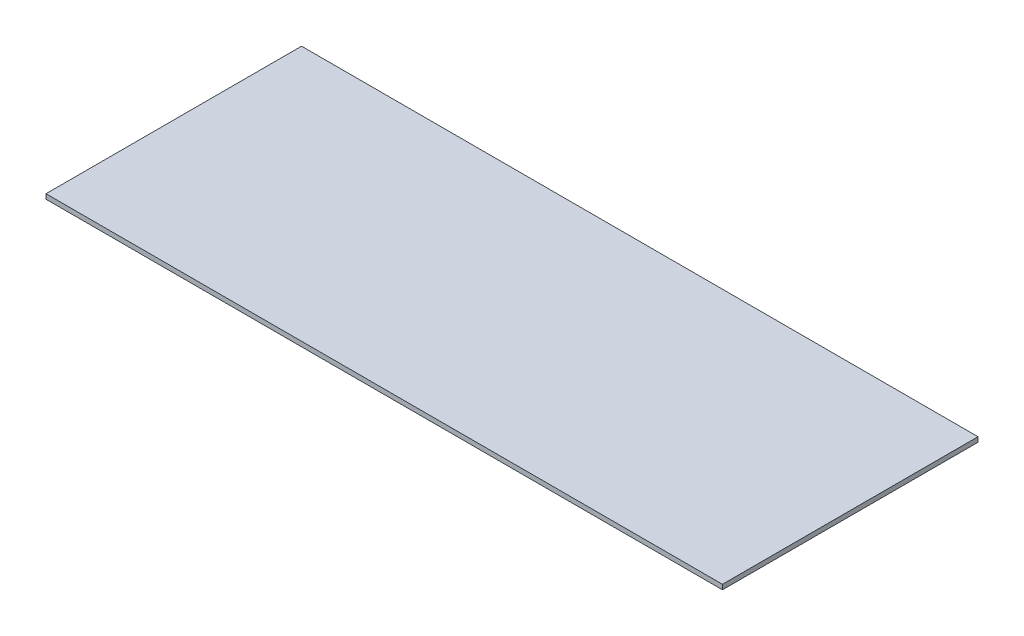
SolidWorks part; units mm, degrees
ref_plane "Front Plane" through (0, 0, 0) normal (0, 0, 1) x (1, 0, 0)
ref_plane "Top Plane" through (0, 0, 0) normal (0, 1, 0) x (1, 0, 0)
ref_plane "Right Plane" through (0, 0, 0) normal (1, 0, 0) x (0, 0, -1)
sketch "Sketch1" plane through (0, 0, 0) normal (0, 1, 0) x (1, 0, 0)
  line L1 (-178.5938, -67.4688) -> (178.5938, -67.4688)
  line L2 (-178.5938, -67.4688) -> (-178.5938, 67.4688)
  line L3 (-178.5938, 67.4688) -> (178.5938, 67.4688)
  line L4 (178.5938, -67.4688) -> (178.5938, 67.4688)
  line L5 (-178.5938, -67.4688) -> (178.5938, 67.4688) construction
  line L6 (-178.5938, 67.4688) -> (178.5938, -67.4688) construction
  point P0 (0, 0)
  dimension "D1" = 134.9375
  dimension "D2" = 357.1875
  dimension "D3" = 0
  dimension "D4" = 0
extrude "Boss-Extrude1" add sketch "Sketch1" along normal blind 2.54
